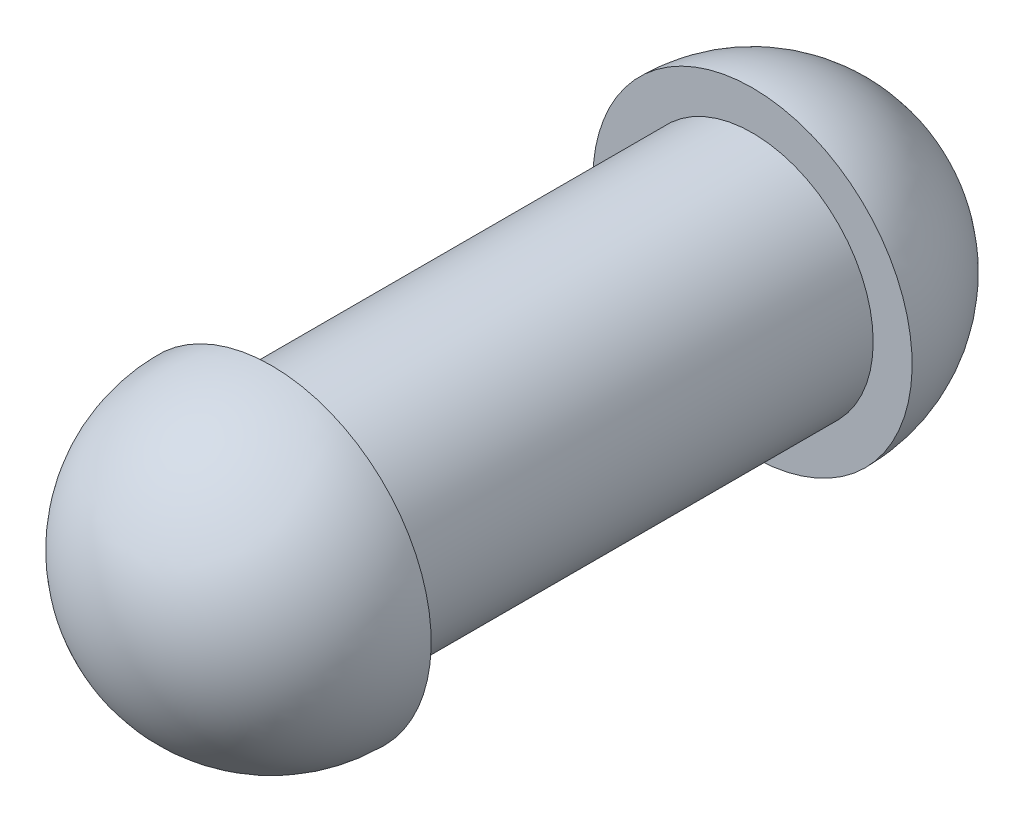
SolidWorks part; units mm, degrees
ref_plane "Front Plane" through (0, 0, 0) normal (0, 0, 1) x (1, 0, 0)
ref_plane "Top Plane" through (0, 0, 0) normal (0, 1, 0) x (1, 0, 0)
ref_plane "Right Plane" through (0, 0, 0) normal (1, 0, 0) x (0, 0, -1)
sketch "Sketch1" plane through (0, 0, 0) normal (0, 0, 1) x (1, 0, 0)
  circle A0 centre (0, 0) radius 15.5
  dimension "D1" = 31
extrude "Boss-Extrude1" add sketch "Sketch1" along normal mid plane 61.75
sketch "Sketch2" plane through (0, 0, 0) normal (1, 0, 0) x (0, 0, -1)
  line L0 (0, 0) -> (-63.0026, 0) construction
  line L1 (-30.875, 15.5) -> (-30.875, -15.5) construction
  line L2 (-51.375, 0) -> (-30.875, 0)
  line L3 (-30.875, 0) -> (-30.875, 20.5)
  line L4 (-30.875, 0) -> (30.875, 0) construction
  arc A0 (-30.875, 20.5) -> (-51.375, 0) centre (-30.875, 0) ccw
  dimension "D1" = 20.5
revolve "Revolve1" add sketch "Sketch2" angle 360 about L0
mirror "Mirror1" about plane through (0, 0, 0) normal (0, 0, 1) of bodies 102
